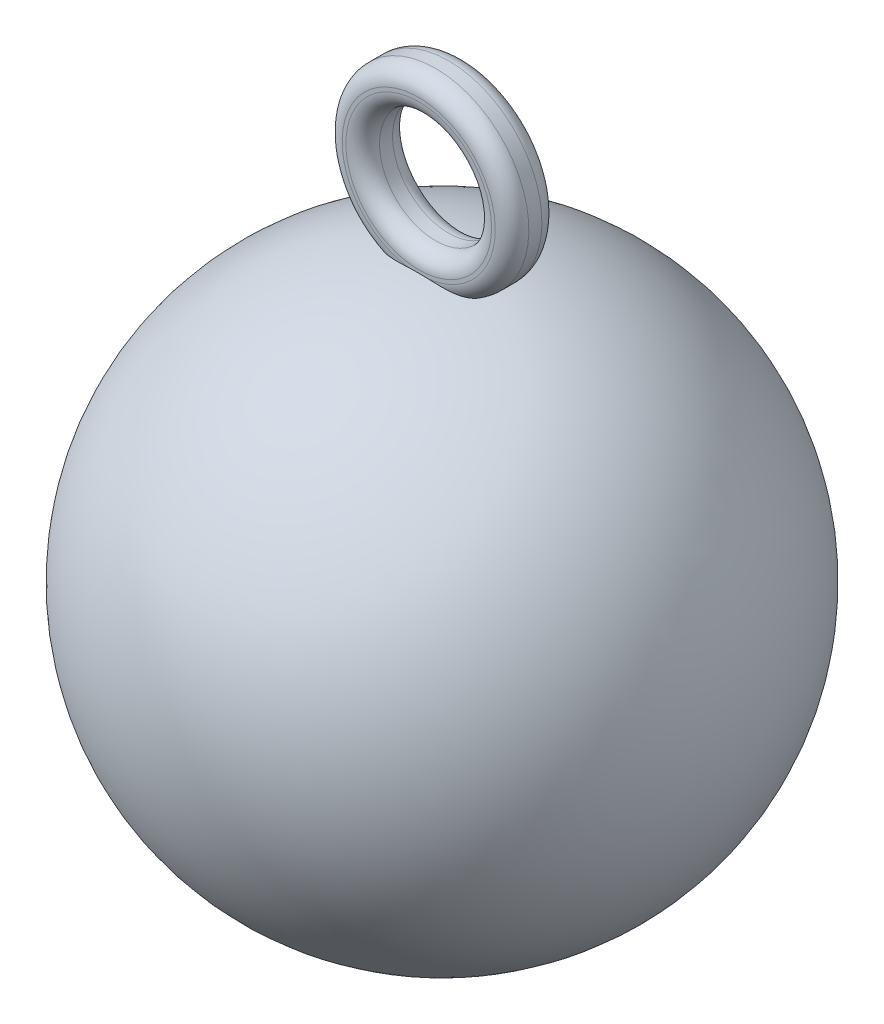
SolidWorks part; units mm, degrees
ref_plane "Piano frontale" through (0, 0, 0) normal (0, 0, 1) x (1, 0, 0)
ref_plane "Piano superiore" through (0, 0, 0) normal (0, 1, 0) x (1, 0, 0)
ref_plane "Piano destro" through (0, 0, 0) normal (1, 0, 0) x (0, 0, -1)
sketch "Schizzo1" plane through (0, 0, 0) normal (0, 0, 1) x (1, 0, 0)
  line L0 (0, 32.4429) -> (0, -30.1711) construction
  line L1 (0, -15) -> (0, 15)
  arc A0 (0, -15) -> (0, 15) centre (0, 0) cw
  dimension "D1" = 15
revolve "Rivoluzione8" add sketch "Schizzo1" angle 360 about L0
sketch "Schizzo2" plane through (0, 0, 0) normal (0, 0, 1) x (1, 0, 0)
  line L0 (0, 29.757) -> (0, -27.6273) construction
  line L1 (0, 24.0043) -> (0, -14.8869) construction
  circle A0 centre (0, 19.0043) radius 5
  circle A1 centre (0, 19.0043) radius 3
  dimension "D1" = 10
extrude "Estrusione-Estrusione1" add sketch "Schizzo2" along normal mid plane 2.5
fillet "Raccordo4" radius 0.9 4 edges at (3, 19.0043, 1.25) (3, 19.0043, -1.25) (0, 24.0043, -1.25) (0, 24.0043, 1.25)
